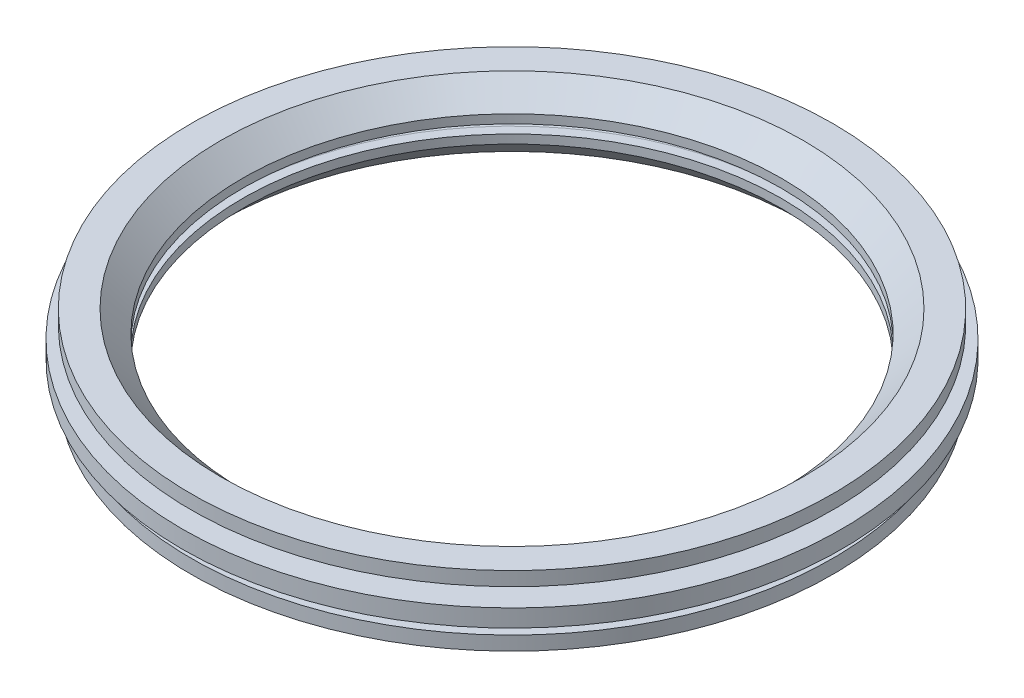
SolidWorks part; units mm, degrees
ref_plane "Front Plane" through (0, 0, 0) normal (0, 0, 1) x (1, 0, 0)
ref_plane "Top Plane" through (0, 0, 0) normal (0, 1, 0) x (1, 0, 0)
ref_plane "Right Plane" through (0, 0, 0) normal (1, 0, 0) x (0, 0, -1)
sketch "Sketch1" plane through (0, 0, 0) normal (0, 0, 1) x (1, 0, 0)
  line L0 (0, 0) -> (0, 33.5731) construction
  line L1 (49.022, 0.7937) -> (49.022, 2.3812)
  line L2 (49.022, 2.3812) -> (52.9908, 6.35)
  line L3 (52.9908, 6.35) -> (58.3565, 6.35)
  line L4 (58.3565, 6.35) -> (58.3565, 3.81)
  line L5 (58.3565, 3.81) -> (53.2765, 3.81)
  line L6 (53.2765, 3.81) -> (53.2765, 1.5875)
  line L7 (53.2765, 1.5875) -> (59.944, 1.5875)
  line L8 (59.944, 1.5875) -> (59.944, 0)
  line L9 (59.944, 0) -> (51.562, 0)
  line L10 (49.022, 0.7937) -> (50.7683, 0.7937)
  line L11 (0, 0) -> (40.5559, 0) construction
  arc A0 (51.562, 0) -> (50.7683, 0.7937) centre (50.7683, 0) ccw
  dimension "D1" = 12.7
  dimension "D2" = 119.888
  dimension "D3" = 98.044
  dimension "D4" = 45
  dimension "D5" = 1.5875
  dimension "D6" = 2.54
  dimension "D7" = 1.5875
  dimension "D8" = 1.5875
  dimension "D9" = 2.54
  dimension "D10" = 1.5875
  dimension "D11" = 5.08
  dimension "D12" = 51.562
revolve "Revolve1" add sketch "Sketch1" angle 360 about L0
mirror "Mirror1" about plane through (0, 0, 0) normal (0, 1, 0) of "Revolve1"
